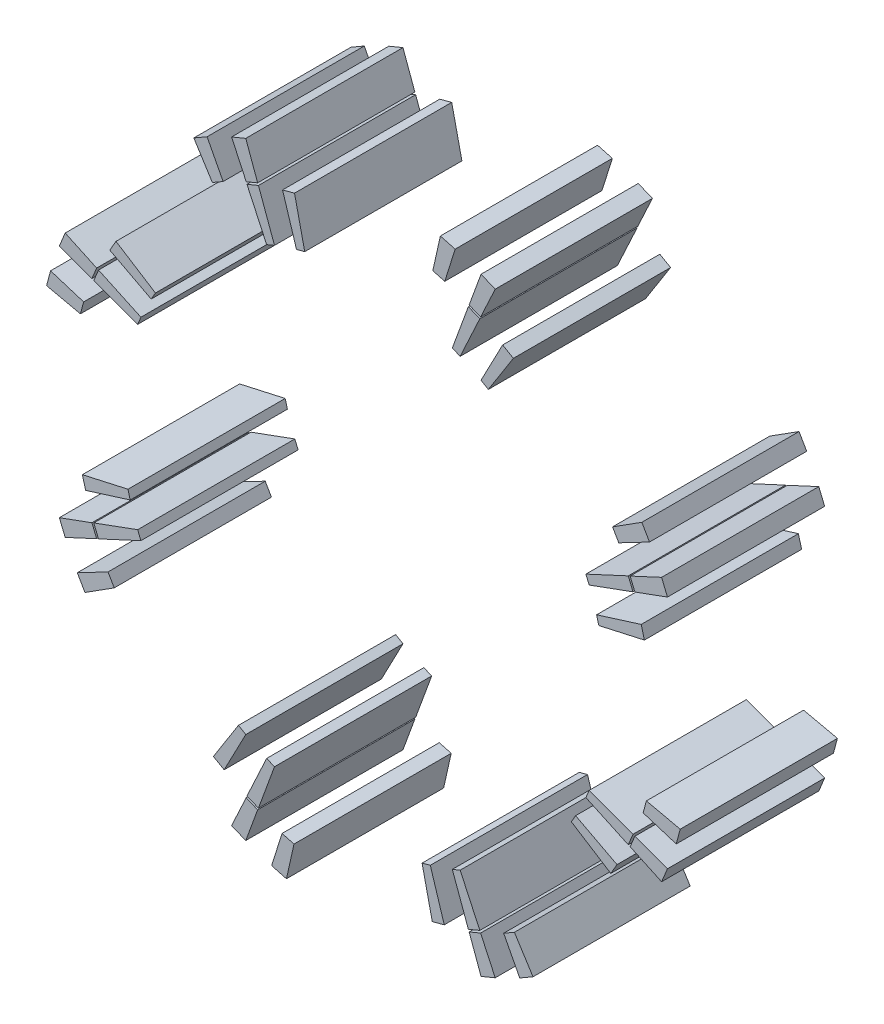
SolidWorks part; units mm, degrees
ref_plane "Спереди" through (0, 0, 0) normal (0, 0, 1) x (1, 0, 0)
ref_plane "Сверху" through (0, 0, 0) normal (0, 1, 0) x (1, 0, 0)
ref_plane "Справа" through (0, 0, 0) normal (1, 0, 0) x (0, 0, -1)
sketch "Эскиз1" plane through (0, 0, 0) normal (0, 0, 1) x (1, 0, 0)
  line L0 (44.9258, 11.1967) -> (53.6252, 13.1443)
  line L1 (53.6252, 13.1443) -> (53.013, 15.4293)
  line L2 (53.013, 15.4293) -> (44.5052, 12.7663)
  line L3 (44.5052, 12.7663) -> (44.9258, 11.1967)
  line L4 (51.8087, 20.1796) -> (58.025, 22.4517)
  line L5 (58.025, 22.4517) -> (56.9056, 25.1541)
  line L6 (56.9056, 25.1541) -> (50.9034, 22.3652)
  line L7 (50.9034, 22.3652) -> (51.8087, 20.1796)
  line L8 (43.08, 16.9649) -> (51.4508, 20.0314)
  line L9 (51.4508, 20.0314) -> (50.5455, 22.2169)
  line L10 (50.5455, 22.2169) -> (42.4581, 18.4662)
  line L11 (42.4581, 18.4662) -> (43.08, 16.9649)
  line L12 (48.7315, 26.7694) -> (54.598, 29.8334)
  line L13 (54.598, 29.8334) -> (53.1355, 32.3666)
  line L14 (53.1355, 32.3666) -> (47.5487, 28.818)
  line L15 (47.5487, 28.818) -> (48.7315, 26.7694)
  line L16 (23.8501, 39.6846) -> (28.6243, 47.2132)
  line L17 (28.6243, 47.2132) -> (26.5757, 48.396)
  line L18 (26.5757, 48.396) -> (22.4428, 40.4971)
  line L19 (22.4428, 40.4971) -> (23.8501, 39.6846)
  line L20 (22.3652, 50.9034) -> (25.1541, 56.9056)
  line L21 (25.1541, 56.9056) -> (22.4517, 58.025)
  line L22 (22.4517, 58.025) -> (20.1796, 51.8087)
  line L23 (20.1796, 51.8087) -> (22.3652, 50.9034)
  line L24 (18.4662, 42.4581) -> (22.2169, 50.5455)
  line L25 (22.2169, 50.5455) -> (20.0314, 51.4508)
  line L26 (20.0314, 51.4508) -> (16.9649, 43.08)
  line L27 (16.9649, 43.08) -> (18.4662, 42.4581)
  line L28 (15.5296, 53.3872) -> (17.5112, 59.7021)
  line L29 (17.5112, 59.7021) -> (14.6859, 60.4591)
  line L30 (14.6859, 60.4591) -> (13.2446, 53.9995)
  line L31 (13.2446, 53.9995) -> (15.5296, 53.3872)
  line L32 (-11.1967, 44.9258) -> (-13.1443, 53.6252)
  line L33 (-13.1443, 53.6252) -> (-15.4293, 53.013)
  line L34 (-15.4293, 53.013) -> (-12.7663, 44.5052)
  line L35 (-12.7663, 44.5052) -> (-11.1967, 44.9258)
  line L36 (-20.1796, 51.8087) -> (-22.4517, 58.025)
  line L37 (-22.4517, 58.025) -> (-25.1541, 56.9056)
  line L38 (-25.1541, 56.9056) -> (-22.3652, 50.9034)
  line L39 (-22.3652, 50.9034) -> (-20.1796, 51.8087)
  line L40 (-16.9649, 43.08) -> (-20.0314, 51.4508)
  line L41 (-20.0314, 51.4508) -> (-22.2169, 50.5455)
  line L42 (-22.2169, 50.5455) -> (-18.4662, 42.4581)
  line L43 (-18.4662, 42.4581) -> (-16.9649, 43.08)
  line L44 (-26.7694, 48.7315) -> (-29.8334, 54.598)
  line L45 (-29.8334, 54.598) -> (-32.3666, 53.1355)
  line L46 (-32.3666, 53.1355) -> (-28.818, 47.5487)
  line L47 (-28.818, 47.5487) -> (-26.7694, 48.7315)
  line L48 (-39.6846, 23.8501) -> (-47.2132, 28.6243)
  line L49 (-47.2132, 28.6243) -> (-48.396, 26.5757)
  line L50 (-48.396, 26.5757) -> (-40.4971, 22.4428)
  line L51 (-40.4971, 22.4428) -> (-39.6846, 23.8501)
  line L52 (-50.9034, 22.3652) -> (-56.9056, 25.1541)
  line L53 (-56.9056, 25.1541) -> (-58.025, 22.4517)
  line L54 (-58.025, 22.4517) -> (-51.8087, 20.1796)
  line L55 (-51.8087, 20.1796) -> (-50.9034, 22.3652)
  line L56 (-42.4581, 18.4662) -> (-50.5455, 22.2169)
  line L57 (-50.5455, 22.2169) -> (-51.4508, 20.0314)
  line L58 (-51.4508, 20.0314) -> (-43.08, 16.9649)
  line L59 (-43.08, 16.9649) -> (-42.4581, 18.4662)
  line L60 (-53.3872, 15.5296) -> (-59.7021, 17.5112)
  line L61 (-59.7021, 17.5112) -> (-60.4591, 14.6859)
  line L62 (-60.4591, 14.6859) -> (-53.9995, 13.2446)
  line L63 (-53.9995, 13.2446) -> (-53.3872, 15.5296)
  line L64 (-44.9258, -11.1967) -> (-53.6252, -13.1443)
  line L65 (-53.6252, -13.1443) -> (-53.013, -15.4293)
  line L66 (-53.013, -15.4293) -> (-44.5052, -12.7663)
  line L67 (-44.5052, -12.7663) -> (-44.9258, -11.1967)
  line L68 (-51.8087, -20.1796) -> (-58.025, -22.4517)
  line L69 (-58.025, -22.4517) -> (-56.9056, -25.1541)
  line L70 (-56.9056, -25.1541) -> (-50.9034, -22.3652)
  line L71 (-50.9034, -22.3652) -> (-51.8087, -20.1796)
  line L72 (-43.08, -16.9649) -> (-51.4508, -20.0314)
  line L73 (-51.4508, -20.0314) -> (-50.5455, -22.2169)
  line L74 (-50.5455, -22.2169) -> (-42.4581, -18.4662)
  line L75 (-42.4581, -18.4662) -> (-43.08, -16.9649)
  line L76 (-48.7315, -26.7694) -> (-54.598, -29.8334)
  line L77 (-54.598, -29.8334) -> (-53.1355, -32.3666)
  line L78 (-53.1355, -32.3666) -> (-47.5487, -28.818)
  line L79 (-47.5487, -28.818) -> (-48.7315, -26.7694)
  line L80 (-23.8501, -39.6846) -> (-28.6243, -47.2132)
  line L81 (-28.6243, -47.2132) -> (-26.5757, -48.396)
  line L82 (-26.5757, -48.396) -> (-22.4428, -40.4971)
  line L83 (-22.4428, -40.4971) -> (-23.8501, -39.6846)
  line L84 (-22.3652, -50.9034) -> (-25.1541, -56.9056)
  line L85 (-25.1541, -56.9056) -> (-22.4517, -58.025)
  line L86 (-22.4517, -58.025) -> (-20.1796, -51.8087)
  line L87 (-20.1796, -51.8087) -> (-22.3652, -50.9034)
  line L88 (-18.4662, -42.4581) -> (-22.2169, -50.5455)
  line L89 (-22.2169, -50.5455) -> (-20.0314, -51.4508)
  line L90 (-20.0314, -51.4508) -> (-16.9649, -43.08)
  line L91 (-16.9649, -43.08) -> (-18.4662, -42.4581)
  line L92 (-15.5296, -53.3872) -> (-17.5112, -59.7021)
  line L93 (-17.5112, -59.7021) -> (-14.6859, -60.4591)
  line L94 (-14.6859, -60.4591) -> (-13.2446, -53.9995)
  line L95 (-13.2446, -53.9995) -> (-15.5296, -53.3872)
  line L96 (11.1967, -44.9258) -> (13.1443, -53.6252)
  line L97 (13.1443, -53.6252) -> (15.4293, -53.013)
  line L98 (15.4293, -53.013) -> (12.7663, -44.5052)
  line L99 (12.7663, -44.5052) -> (11.1967, -44.9258)
  line L100 (20.1796, -51.8087) -> (22.4517, -58.025)
  line L101 (22.4517, -58.025) -> (25.1541, -56.9056)
  line L102 (25.1541, -56.9056) -> (22.3652, -50.9034)
  line L103 (22.3652, -50.9034) -> (20.1796, -51.8087)
  line L104 (16.9649, -43.08) -> (20.0314, -51.4508)
  line L105 (20.0314, -51.4508) -> (22.2169, -50.5455)
  line L106 (22.2169, -50.5455) -> (18.4662, -42.4581)
  line L107 (18.4662, -42.4581) -> (16.9649, -43.08)
  line L108 (26.7694, -48.7315) -> (29.8334, -54.598)
  line L109 (29.8334, -54.598) -> (32.3666, -53.1355)
  line L110 (32.3666, -53.1355) -> (28.818, -47.5487)
  line L111 (28.818, -47.5487) -> (26.7694, -48.7315)
  line L112 (39.6846, -23.8501) -> (47.2132, -28.6243)
  line L113 (47.2132, -28.6243) -> (48.396, -26.5757)
  line L114 (48.396, -26.5757) -> (40.4971, -22.4428)
  line L115 (40.4971, -22.4428) -> (39.6846, -23.8501)
  line L116 (50.9034, -22.3652) -> (56.9056, -25.1541)
  line L117 (56.9056, -25.1541) -> (58.025, -22.4517)
  line L118 (58.025, -22.4517) -> (51.8087, -20.1796)
  line L119 (51.8087, -20.1796) -> (50.9034, -22.3652)
  line L120 (42.4581, -18.4662) -> (50.5455, -22.2169)
  line L121 (50.5455, -22.2169) -> (51.4508, -20.0314)
  line L122 (51.4508, -20.0314) -> (43.08, -16.9649)
  line L123 (43.08, -16.9649) -> (42.4581, -18.4662)
  line L124 (53.3872, -15.5296) -> (59.7021, -17.5112)
  line L125 (59.7021, -17.5112) -> (60.4591, -14.6859)
  line L126 (60.4591, -14.6859) -> (53.9995, -13.2446)
  line L127 (53.9995, -13.2446) -> (53.3872, -15.5296)
extrude "Slot_copper_envelopes" add sketch "Эскиз1" along normal blind 30 from offset 15 separate body
